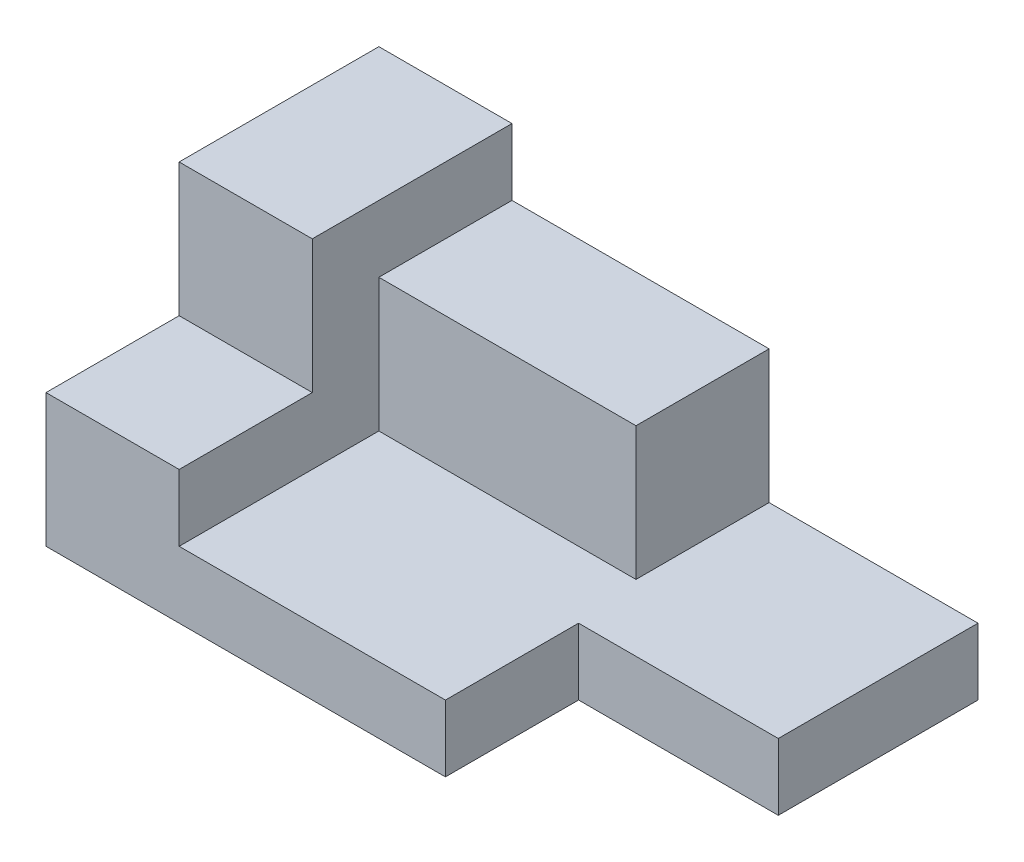
SolidWorks part; units mm, degrees
ref_plane "Front Plane" through (0, 0, 0) normal (0, 0, 1) x (1, 0, 0)
ref_plane "Top Plane" through (0, 0, 0) normal (0, 1, 0) x (1, 0, 0)
ref_plane "Right Plane" through (0, 0, 0) normal (1, 0, 0) x (0, 0, -1)
sketch "Sketch1" plane through (0, 0, 0) normal (0, 1, 0) x (1, 0, 0)
  line L0 (0, 0) -> (60, 0)
  line L1 (60, 0) -> (60, 20)
  line L2 (60, 20) -> (90, 20)
  line L3 (90, 20) -> (90, 50)
  line L4 (90, 50) -> (60, 50)
  line L5 (60, 50) -> (0, 50)
  line L6 (0, 50) -> (0, 0)
  dimension "D1" = 60
  dimension "D2" = 20
  dimension "D3" = 30
  dimension "D4" = 50
  dimension "D5" = 60
  dimension "D6" = 30
extrude "Boss-Extrude2" add sketch "Sketch1" along normal blind 10
sketch "Sketch2" plane through (0, 10, 0) normal (0, 1, 0) x (1, 0, 0)
  line L0 (90, 50) -> (0, 50) construction
  line L1 (0, 0) -> (20, 0)
  line L2 (0, 0) -> (0, 20)
  line L3 (0, 20) -> (20, 20)
  line L4 (20, 0) -> (20, 20)
  line L5 (58.1349, 50) -> (18.1349, 50)
  line L6 (58.1349, 50) -> (58.1349, 30)
  line L7 (58.1349, 30) -> (18.1349, 30)
  line L8 (18.1349, 50) -> (18.1349, 30)
  dimension "D1" = 20
  dimension "D2" = 20
  dimension "D3" = 40
  dimension "D4" = 20
extrude "Boss-Extrude3" add sketch "Sketch2" along normal blind 10 contours L2 L1 L4 L3
sketch "Sketch3" plane through (0, 10, 0) normal (0, 1, 0) x (1, 0, 0)
  line L0 (90, 50) -> (0, 50) construction
  line L1 (58.6224, 50) -> (18.6224, 50)
  line L2 (58.6224, 50) -> (58.6224, 30)
  line L3 (58.6224, 30) -> (18.6224, 30)
  line L4 (18.6224, 50) -> (18.6224, 30)
  dimension "D1" = 40
  dimension "D2" = 20
extrude "Boss-Extrude4" add sketch "Sketch3" along normal blind 20 contours L2 L1 L4 L3
sketch "Sketch4" plane through (0, 10, 0) normal (0, 1, 0) x (1, 0, 0)
  line L0 (0, 20) -> (20, 20) construction
  line L1 (0, 50) -> (20, 50)
  line L2 (0, 50) -> (0, 20)
  line L3 (0, 20) -> (20, 20)
  line L4 (20, 50) -> (20, 20)
  dimension "D1" = 30
  dimension "D2" = 20
extrude "Boss-Extrude6" add sketch "Sketch4" along normal blind 30
